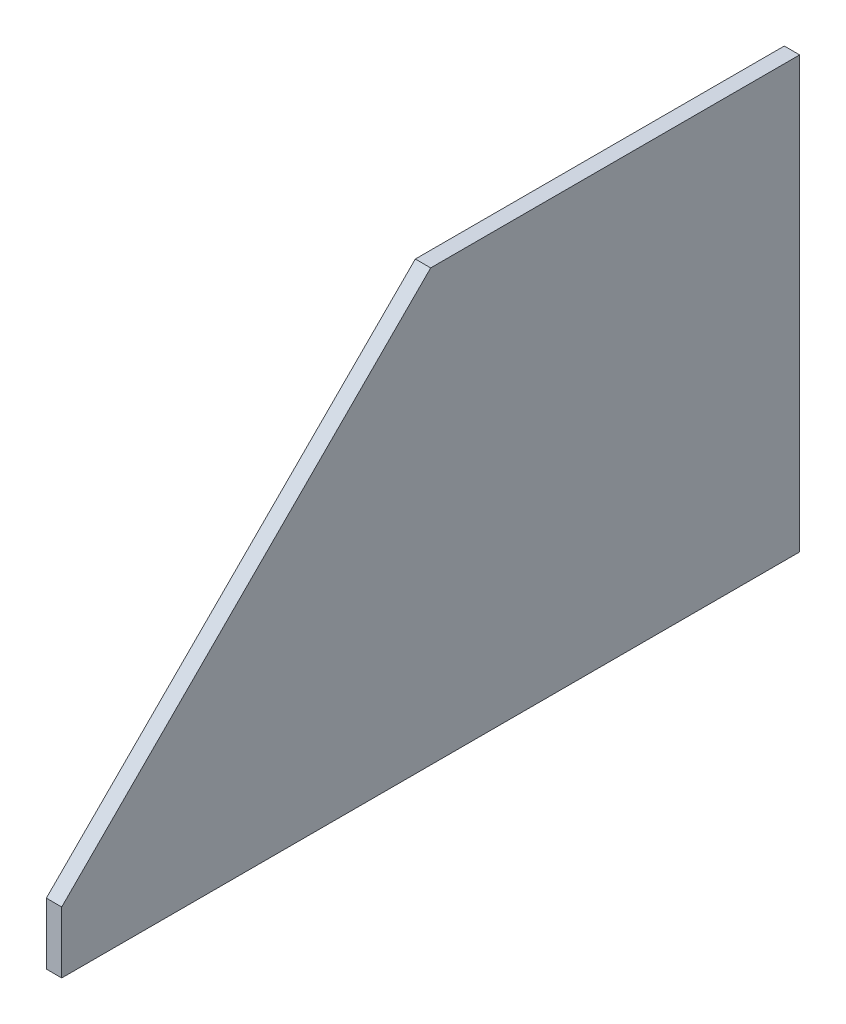
SolidWorks part; units mm, degrees
ref_plane "Plan de face" through (0, 0, 0) normal (0, 0, 1) x (1, 0, 0)
ref_plane "Plan de dessus" through (0, 0, 0) normal (0, 1, 0) x (1, 0, 0)
ref_plane "Plan de droite" through (0, 0, 0) normal (1, 0, 0) x (0, 0, -1)
sketch "Esquisse2" plane through (0, 0, 0) normal (1, 0, 0) x (0, 0, -1)
  line L0 (0, 0) -> (-304.8, 0)
  line L1 (-304.8, 0) -> (-152.4, 152.4)
  line L2 (-152.4, 152.4) -> (0, 152.4)
  line L3 (0, 152.4) -> (0, 0)
  line L4 (0, -25.4) -> (-304.8, -25.4)
  line L5 (-304.8, -25.4) -> (-304.8, 0)
  line L6 (0, -25.4) -> (0, 0)
  dimension "D1" = 25.4
  dimension "D2" = 152.4
  dimension "D3" = 152.4
  dimension "D4" = 304.8
extrude "Boss.-Extru.1" add sketch "Esquisse2" along normal blind 6.35 contours L3 L2 L1 L0 | L4 L6 L0 L5
